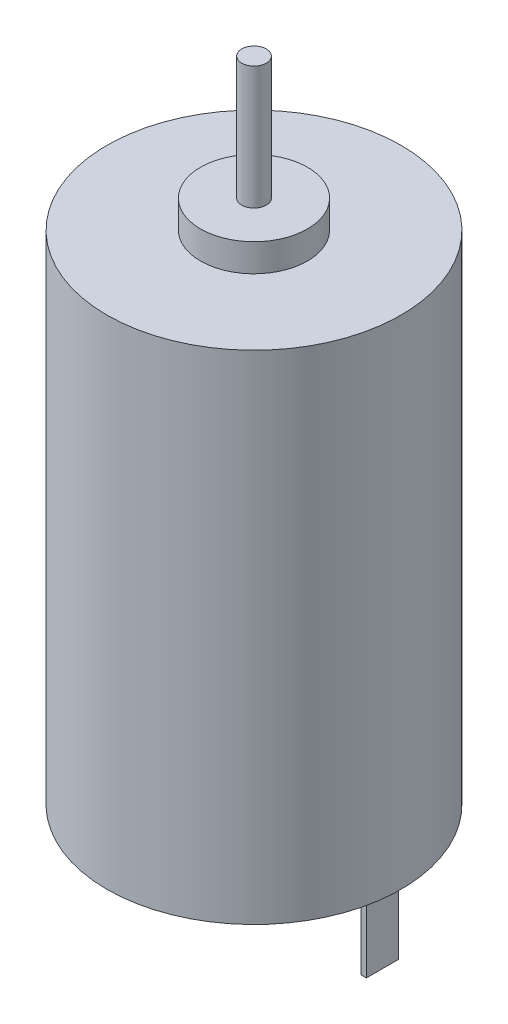
SolidWorks part; units mm, degrees
ref_plane "Front Plane" through (0, 0, 0) normal (0, 0, 1) x (1, 0, 0)
ref_plane "Top Plane" through (0, 0, 0) normal (0, 1, 0) x (1, 0, 0)
ref_plane "Right Plane" through (0, 0, 0) normal (1, 0, 0) x (0, 0, -1)
sketch "Sketch1" plane through (0, 0, 0) normal (0, 1, 0) x (1, 0, 0)
  circle A0 centre (0, 0) radius 13.75
  dimension "D1" = 27.5
extrude "Boss-Extrude1" add sketch "Sketch1" along normal blind 46.5
sketch "Sketch2" plane through (0, 0, 0) normal (0, -1, 0) x (1, 0, 0)
  circle A0 centre (0, 0) radius 5
  dimension "D1" = 10
extrude "Boss-Extrude2" add sketch "Sketch2" along normal blind 2.6
sketch "Sketch3" plane through (0, 0, 0) normal (0, -1, 0) x (1, 0, 0)
  line L0 (0, 13.75) -> (0, 0) construction
  line L1 (-12, 1.5) -> (-11.5, 1.5)
  line L2 (-12, 1.5) -> (-12, -1.5)
  line L3 (-12, -1.5) -> (-11.5, -1.5)
  line L4 (-11.5, 1.5) -> (-11.5, -1.5)
  line L5 (12, -1.5) -> (11.5, -1.5)
  line L6 (11.5, 1.5) -> (11.5, -1.5)
  line L7 (12, 1.5) -> (11.5, 1.5)
  line L8 (12, 1.5) -> (12, -1.5)
  circle A0 centre (0, 0) radius 13.75 construction
  point P9 (-11.5, 0)
  point P12 (-9.9911, 1.6315)
  dimension "D1" = 3
  dimension "D2" = 0.5
  dimension "D3" = 11.5
extrude "Boss-Extrude3" add sketch "Sketch3" along normal blind 7.3 separate body
sketch "Sketch4" plane through (0, 46.5, 0) normal (0, 1, 0) x (1, 0, 0)
  circle A0 centre (0, 0) radius 5
  dimension "D1" = 10
extrude "Boss-Extrude4" add sketch "Sketch4" along normal blind 2.6
sketch "Sketch5" plane through (0, 49.1, 0) normal (0, 1, 0) x (1, 0, 0)
  circle A0 centre (0, 0) radius 1.15
  dimension "D1" = 2.3
extrude "Boss-Extrude5" add sketch "Sketch5" along normal blind 11.5 separate body
